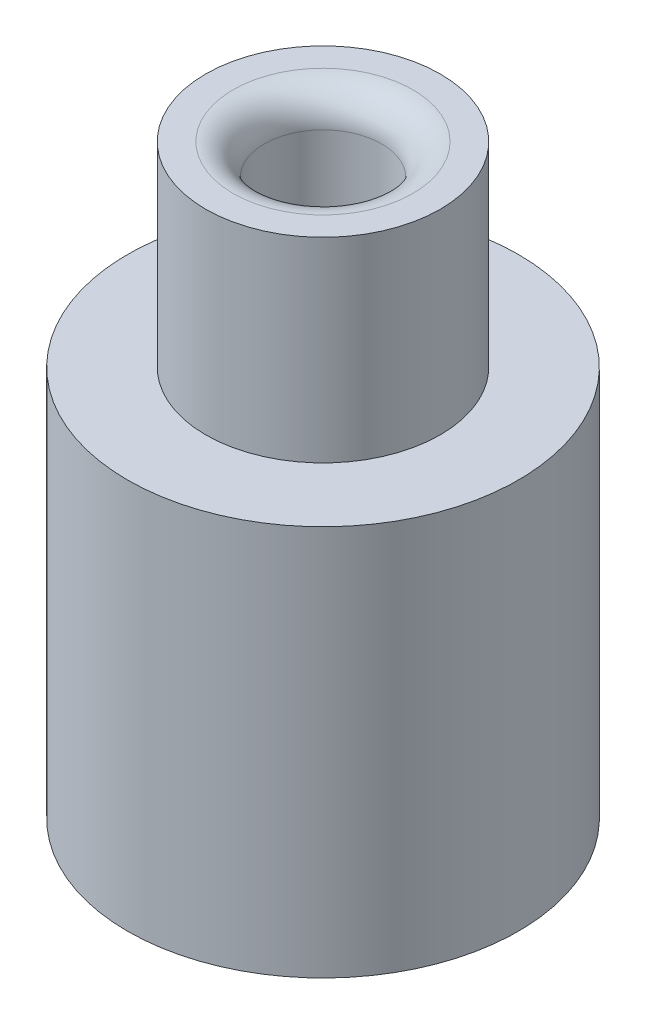
SolidWorks part; units mm, degrees
ref_plane "Front Plane" through (0, 0, 0) normal (0, 0, 1) x (1, 0, 0)
ref_plane "Top Plane" through (0, 0, 0) normal (0, 1, 0) x (1, 0, 0)
ref_plane "Right Plane" through (0, 0, 0) normal (1, 0, 0) x (0, 0, -1)
sketch "Esquisse1" plane through (0, 0, 0) normal (0, 1, 0) x (1, 0, 0)
  circle A0 centre (0, 0) radius 5
extrude "Boss.-Extru.1" add sketch "Esquisse1" along normal blind 6 and the other way blind 4
sketch "Esquisse2" plane through (0, 6, 0) normal (0, 1, 0) x (1, 0, 0)
  circle A0 centre (0, 0) radius 3
extrude "Boss.-Extru.2" add sketch "Esquisse2" along normal blind 5 and the other way blind 1
sketch "Esquisse3" plane through (0, 11, 0) normal (0, 1, 0) x (1, 0, 0)
  circle A0 centre (0, 0) radius 1.5
extrude "Enlèv. mat.-Extru.2" cut sketch "Esquisse3" against normal blind 10
sketch "Esquisse4" plane through (0, -4, 0) normal (0, -1, 0) x (1, 0, 0)
  circle A0 centre (0, 0) radius 2.5
extrude "Enlèv. mat.-Extru.3" cut sketch "Esquisse4" against normal blind 5
fillet "Congé1" radius 0.8 1 edges at (0, 11, 1.5)
